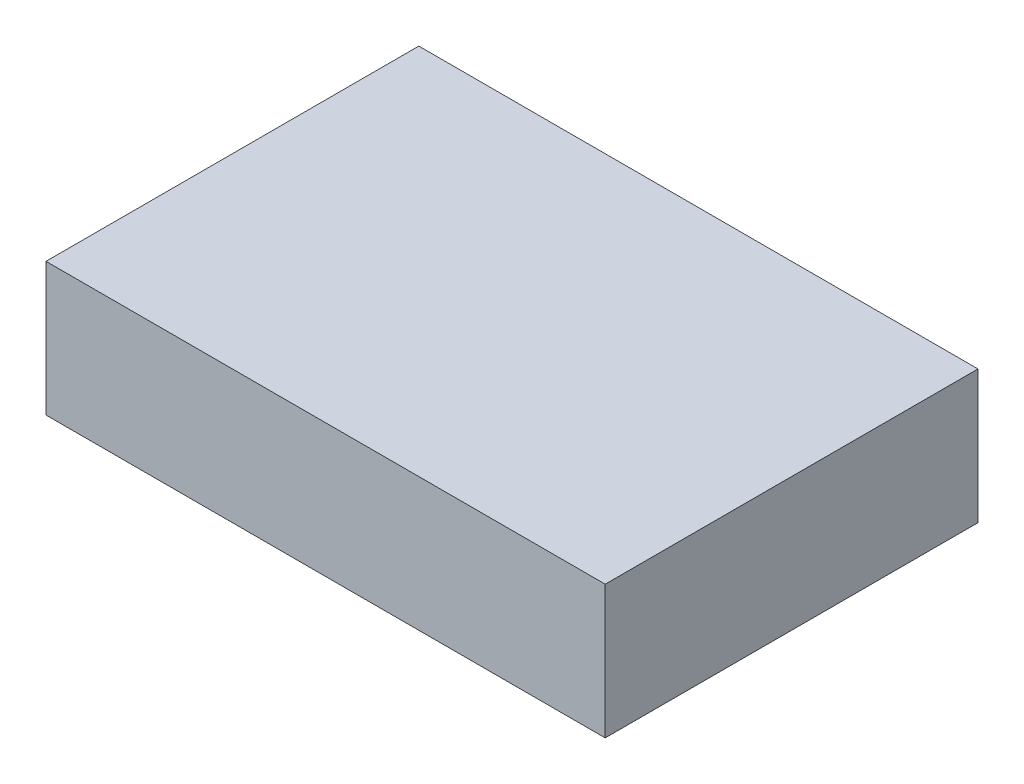
SolidWorks part; units mm, degrees
ref_plane "前视基准面" through (0, 0, 0) normal (0, 0, 1) x (1, 0, 0)
ref_plane "上视基准面" through (0, 0, 0) normal (0, 1, 0) x (1, 0, 0)
ref_plane "右视基准面" through (0, 0, 0) normal (1, 0, 0) x (0, 0, -1)
sketch "草图1" plane through (0, 0, 0) normal (0, 1, 0) x (1, 0, 0)
  line L1 (-10.5, 7) -> (10.5, 7)
  line L2 (-10.5, 7) -> (-10.5, -7)
  line L3 (-10.5, -7) -> (10.5, -7)
  line L4 (10.5, 7) -> (10.5, -7)
  line L5 (-10.5, 7) -> (10.5, -7) construction
  line L6 (-10.5, -7) -> (10.5, 7) construction
  point P0 (0, 0)
  dimension "D1" = 21
  dimension "D2" = 14
extrude "凸台-拉伸1" add sketch "草图1" along normal blind 5
